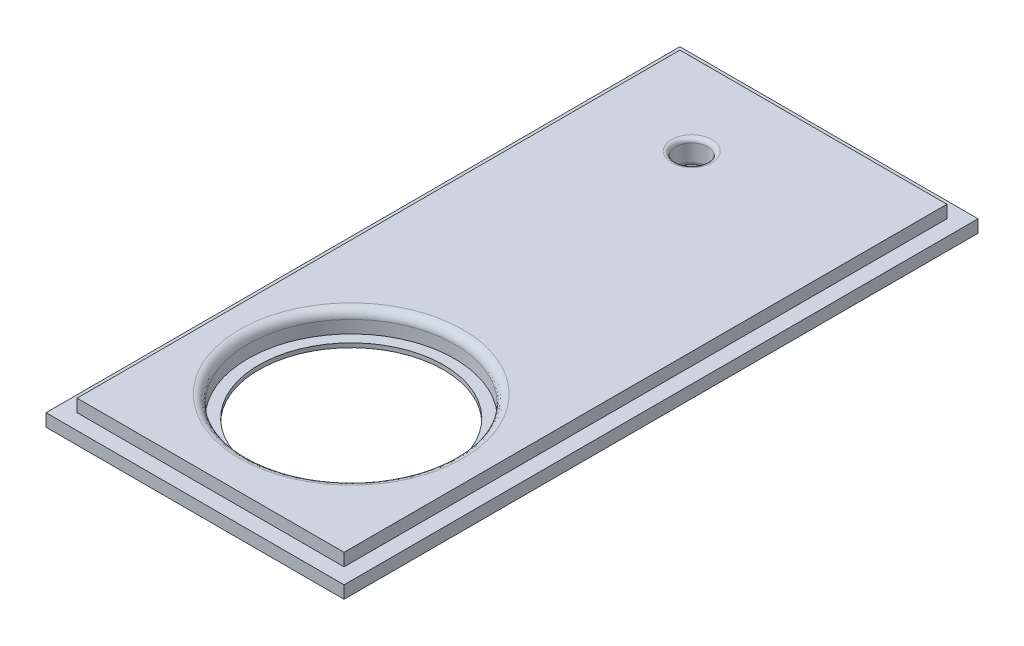
SolidWorks part; units mm, degrees
ref_plane "Front Plane" through (0, 0, 0) normal (0, 0, 1) x (1, 0, 0)
ref_plane "Top Plane" through (0, 0, 0) normal (0, 1, 0) x (1, 0, 0)
ref_plane "Right Plane" through (0, 0, 0) normal (1, 0, 0) x (0, 0, -1)
sketch "Sketch1" plane through (0, 0, 0) normal (0, 1, 0) x (1, 0, 0)
  line L1 (0, 0) -> (35.5, 0)
  line L2 (0, 0) -> (0, 75.5)
  line L3 (0, 75.5) -> (35.5, 75.5)
  line L4 (35.5, 0) -> (35.5, 75.5)
  dimension "D1" = 75.5
  dimension "D2" = 35.5
extrude "Boss-Extrude1" add sketch "Sketch1" along normal blind 1.5 contours L2 L1 L4 L3
sketch3d "3DSketch1"
  line L0 (1.85, 1.5, -1.85) -> (33.65, 1.5, -1.85)
  line L1 (33.65, 1.5, -1.85) -> (33.65, 1.5, -73.65)
  line L2 (33.65, 1.5, -73.65) -> (1.85, 1.5, -73.65)
  line L3 (1.85, 1.5, -73.65) -> (1.85, 1.5, -1.85)
  line L4 (1.85, 1.5, -1.85) -> (33.65, 1.5, -1.85)
  line L5 (33.65, 1.5, -1.85) -> (33.65, 1.5, -73.65)
  line L6 (33.65, 1.5, -73.65) -> (1.85, 1.5, -73.65)
  line L7 (1.85, 1.5, -73.65) -> (1.85, 1.5, -1.85)
  dimension "D1" = 1.85
extrude "Boss-Extrude2" add sketch "3DSketch1" along direction (0, 1, 0) on the side of the normal blind 1.5 contours L4 L5 L6 L7
sketch "Sketch2" plane through (0, 3, 0) normal (0, 1, 0) x (1, 0, 0)
  line L0 (17.75, 1.85) -> (17.75, 18.6) construction
  line L1 (1.85, 1.85) -> (33.65, 1.85) construction
  circle A0 centre (17.75, 18.6) radius 11
  dimension "D1" = 16.75
extrude "Cut-Extrude1" cut sketch "Sketch2" against normal blind 10 contours A0
sketch3d "3DSketch2"
  line L1 (17.75, 0, -18.6) -> (17.75, 3, -18.6) construction
  circle A1 centre (17.75, 3, -18.6) radius 11
  spline S0 degree 3 poles (20.9787, 3, -6.5842) (17.7842, 3, -6.1625) (14.6249, 3, -6.5662) (11.6682, 3, -7.7508) (9.0825, 3, -9.6737) (7.0631, 3, -12.2286) (5.7759, 3, -15.2201) (5.3089, 3, -18.4431) (5.6944, 3, -21.6769) (6.9058, 3, -24.6999) (8.8602, 3, -27.3049) (11.4236, 3, -29.3136) (14.4204, 3, -30.5882) (17.6454, 3, -31.0417) (20.8775, 3, -30.6425) (23.8954, 3, -29.4185) (26.4922, 3, -27.4531) (28.4901, 3, -24.8813) (29.7521, 3, -21.8791) (30.192, 3, -18.6523) (29.7793, 3, -15.4219) (28.5426, 3, -12.4092) (26.5663, 3, -9.8207) (23.9861, 3, -7.8336) (20.9787, 3, -6.5842) (17.7842, 3, -6.1625) (14.6249, 3, -6.5662) knots -0.125333 -0.083555 -0.041778 0 0.040443 0.080894 0.122671 0.164449 0.206226 0.248004 0.289781 0.331559 0.373337 0.415114 0.456892 0.498669 0.540447 0.582224 0.624002 0.665779 0.707557 0.749335 0.791112 0.83289 0.874667 0.916445 0.958222 1 1.040443 1.080894 1.122671 only from (17.75, 3, -6.3) to (17.75, 3, -6.3)
  spline S1 degree 3 poles (20.9787, 3, -6.5842) (17.7842, 3, -6.1625) (14.6249, 3, -6.5662) (11.6682, 3, -7.7508) (9.0825, 3, -9.6737) (7.0631, 3, -12.2286) (5.7759, 3, -15.2201) (5.3089, 3, -18.4431) (5.6944, 3, -21.6769) (6.9058, 3, -24.6999) (8.8602, 3, -27.3049) (11.4236, 3, -29.3136) (14.4204, 3, -30.5882) (17.6454, 3, -31.0417) (20.8775, 3, -30.6425) (23.8954, 3, -29.4185) (26.4922, 3, -27.4531) (28.4901, 3, -24.8813) (29.7521, 3, -21.8791) (30.192, 3, -18.6523) (29.7793, 3, -15.4219) (28.5426, 3, -12.4092) (26.5663, 3, -9.8207) (23.9861, 3, -7.8336) (20.9787, 3, -6.5842) (17.7842, 3, -6.1625) (14.6249, 3, -6.5662) knots -0.125333 -0.083555 -0.041778 0 0.040443 0.080894 0.122671 0.164449 0.206226 0.248004 0.289781 0.331559 0.373337 0.415114 0.456892 0.498669 0.540447 0.582224 0.624002 0.665779 0.707557 0.749335 0.791112 0.83289 0.874667 0.916445 0.958222 1 1.040443 1.080894 1.122671 only from (17.75, 3, -6.3) to (17.75, 3, -6.3)
  point P3 (17.75, 14, -18.6)
  dimension "D1" = 1.3
extrude "Cut-Extrude2" cut sketch "3DSketch2" along direction (0, 1, 0) on the side of the normal blind 2.5 contours A1 | S1
sketch "Sketch4" plane through (0, 3, 0) normal (0, 1, 0) x (1, 0, 0)
  line L0 (1.85, 63.925) -> (12.975, 63.925) construction
  line L1 (1.85, 73.65) -> (1.85, 1.85) construction
  line L2 (12.975, 73.65) -> (12.975, 63.925) construction
  line L3 (33.65, 73.65) -> (1.85, 73.65) construction
  circle A0 centre (12.975, 63.925) radius 1.9
  dimension "D2" = 11.125
  dimension "D1" = 9.725
extrude "Cut-Extrude3" cut sketch "Sketch4" against normal blind 6
fillet "Fillet1" radius 0.5 1 edges at (12.975, 3, -62.025)
fillet "Fillet2" radius 0.5 1 edges at (12.975, 0, -62.025)
fillet "Fillet3" radius 1 1 edges
